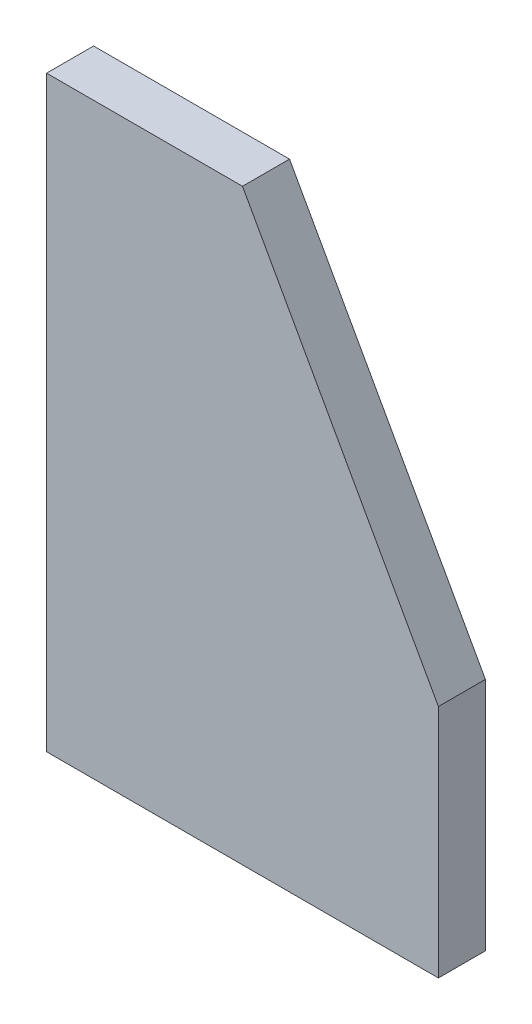
SolidWorks part; units mm, degrees
material "Galvanized Steel"
ref_plane "Front Plane" through (0, 0, 0) normal (0, 0, 1) x (1, 0, 0)
ref_plane "Top Plane" through (0, 0, 0) normal (0, 1, 0) x (1, 0, 0)
ref_plane "Right Plane" through (0, 0, 0) normal (1, 0, 0) x (0, 0, -1)
sketch "Sketch1" plane through (0, 0, 0) normal (0, 0, 1) x (1, 0, 0)
  line L0 (0, 37.5) -> (25, -7.5)
  line L1 (-25, -37.5) -> (25, -37.5)
  line L2 (-25, -37.5) -> (-25, 37.5)
  line L3 (-25, 37.5) -> (0, 37.5)
  line L4 (25, -37.5) -> (25, -7.5)
  line L5 (-25, -37.5) -> (25, 37.5) construction
  line L6 (-25, 37.5) -> (25, -37.5) construction
  point P0 (0, 0)
  dimension "D1" = 75
  dimension "D2" = 50
  dimension "D3" = 25
  dimension "D4" = 45
extrude "Boss-Extrude1" add sketch "Sketch1" along normal mid plane 6 contours L0 L4 L1 L2 L3
